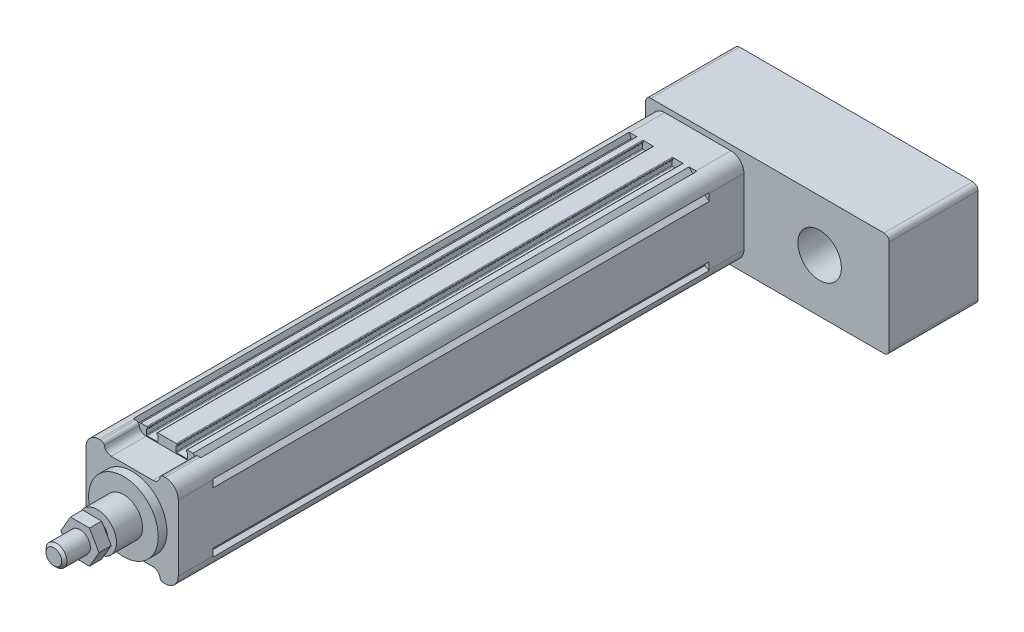
SolidWorks part; units mm, degrees
ref_plane "Front" through (0, 0, 0) normal (0, 0, 1) x (1, 0, 0)
ref_plane "Top" through (0, 0, 0) normal (0, 1, 0) x (1, 0, 0)
ref_plane "Right" through (0, 0, 0) normal (1, 0, 0) x (0, 0, -1)
sketch "草图1" plane through (0, 0, 0) normal (0, 0, 1) x (1, 0, 0)
  line L0 (19.7737, 3) -> (23.3, 3)
  line L1 (23.3, 3) -> (23.3, -3)
  line L2 (23.3, -3) -> (19.7737, -3)
  line L3 (-19.7737, -3) -> (-23.3, -3)
  line L4 (-23.3, -3) -> (-23.3, 3)
  line L5 (-23.3, 3) -> (-19.7737, 3)
  line L6 (-18.2, 24) -> (-19.4434, 26.4869)
  line L7 (-26.4869, 19.4434) -> (-24, 18.2)
  line L8 (-24, 18.2) -> (-24, 17.1)
  line L9 (-24, 17.1) -> (-26.5, 15)
  line L10 (-26.5, 15) -> (-26.5, -15)
  line L11 (-26.5, -15) -> (-24, -17.1)
  line L12 (-24, -17.1) -> (-24, -18.2)
  line L13 (-24, -18.2) -> (-26.4869, -19.4434)
  line L14 (-19.4434, -26.4869) -> (-18.2, -24)
  line L15 (-18.2, -24) -> (-17.1, -24)
  line L16 (-17.1, -24) -> (-15, -26.5)
  line L17 (-15, -26.5) -> (-11.65, -26.5)
  line L18 (-11.25, -26.1) -> (-11.25, -25.6)
  line L19 (-11.65, -25.2) -> (-11.75, -25.2)
  line L20 (-11.75, -25.2) -> (-11.75, -22.4)
  line L21 (-11.35, -22) -> (-5.65, -22)
  line L22 (-5.25, -22.4) -> (-5.25, -25.2)
  line L23 (-5.25, -25.2) -> (-5.35, -25.2)
  line L24 (-5.75, -25.6) -> (-5.75, -26.1)
  line L25 (-5.35, -26.5) -> (5.35, -26.5)
  line L26 (5.75, -26.1) -> (5.75, -25.6)
  line L27 (5.35, -25.2) -> (5.25, -25.2)
  line L28 (5.25, -25.2) -> (5.25, -22.4)
  line L29 (5.65, -22) -> (11.35, -22)
  line L30 (11.75, -22.4) -> (11.75, -25.2)
  line L31 (11.75, -25.2) -> (11.65, -25.2)
  line L32 (11.25, -25.6) -> (11.25, -26.1)
  line L33 (11.65, -26.5) -> (15, -26.5)
  line L34 (15, -26.5) -> (17.1, -24)
  line L35 (17.1, -24) -> (18.2, -24)
  line L36 (18.2, -24) -> (19.4434, -26.4869)
  line L37 (26.4869, -19.4434) -> (24, -18.2)
  line L38 (24, -18.2) -> (24, -17.1)
  line L39 (24, -17.1) -> (26.5, -15)
  line L40 (26.5, -15) -> (26.5, 15)
  line L41 (26.5, 15) -> (24, 17.1)
  line L42 (24, 17.1) -> (24, 18.2)
  line L43 (24, 18.2) -> (26.4869, 19.4434)
  line L44 (19.4434, 26.4869) -> (18.2, 24)
  line L45 (18.2, 24) -> (17.1, 24)
  line L46 (17.1, 24) -> (15, 26.5)
  line L47 (15, 26.5) -> (11.65, 26.5)
  line L48 (11.25, 26.1) -> (11.25, 25.6)
  line L49 (11.65, 25.2) -> (11.75, 25.2)
  line L50 (11.75, 25.2) -> (11.75, 22.4)
  line L51 (11.35, 22) -> (5.65, 22)
  line L52 (5.25, 22.4) -> (5.25, 25.2)
  line L53 (5.25, 25.2) -> (5.35, 25.2)
  line L54 (5.75, 25.6) -> (5.75, 26.1)
  line L55 (5.35, 26.5) -> (-5.35, 26.5)
  line L56 (-5.75, 26.1) -> (-5.75, 25.6)
  line L57 (-5.35, 25.2) -> (-5.25, 25.2)
  line L58 (-5.25, 25.2) -> (-5.25, 22.4)
  line L59 (-5.65, 22) -> (-11.35, 22)
  line L60 (-11.75, 22.4) -> (-11.75, 25.2)
  line L61 (-11.75, 25.2) -> (-11.65, 25.2)
  line L62 (-11.25, 25.6) -> (-11.25, 26.1)
  line L63 (-11.65, 26.5) -> (-15, 26.5)
  line L64 (-15, 26.5) -> (-17.1, 24)
  line L65 (-17.1, 24) -> (-18.2, 24)
  arc A0 (19.7737, 3) -> (-19.7737, 3) centre (0, 0) ccw
  arc A1 (-19.7737, -3) -> (19.7737, -3) centre (0, 0) ccw
  circle A2 centre (19, 19) radius 2.1
  circle A3 centre (19, -19) radius 2.1
  circle A4 centre (-19, -19) radius 2.1
  circle A5 centre (-19, 19) radius 2.1
  arc A6 (-19.4434, 26.4869) -> (-26.4869, 19.4434) centre (-19, 19) ccw
  arc A7 (-26.4869, -19.4434) -> (-19.4434, -26.4869) centre (-19, -19) ccw
  arc A8 (-11.65, -26.5) -> (-11.25, -26.1) centre (-11.65, -26.1) ccw
  arc A9 (-11.25, -25.6) -> (-11.65, -25.2) centre (-11.65, -25.6) ccw
  arc A10 (-11.35, -22) -> (-11.75, -22.4) centre (-11.35, -22.4) ccw
  arc A11 (-5.25, -22.4) -> (-5.65, -22) centre (-5.65, -22.4) ccw
  arc A12 (-5.35, -25.2) -> (-5.75, -25.6) centre (-5.35, -25.6) ccw
  arc A13 (-5.75, -26.1) -> (-5.35, -26.5) centre (-5.35, -26.1) ccw
  arc A14 (5.35, -26.5) -> (5.75, -26.1) centre (5.35, -26.1) ccw
  arc A15 (5.75, -25.6) -> (5.35, -25.2) centre (5.35, -25.6) ccw
  arc A16 (5.65, -22) -> (5.25, -22.4) centre (5.65, -22.4) ccw
  arc A17 (11.75, -22.4) -> (11.35, -22) centre (11.35, -22.4) ccw
  arc A18 (11.65, -25.2) -> (11.25, -25.6) centre (11.65, -25.6) ccw
  arc A19 (11.25, -26.1) -> (11.65, -26.5) centre (11.65, -26.1) ccw
  arc A20 (19.4434, -26.4869) -> (26.4869, -19.4434) centre (19, -19) ccw
  arc A21 (26.4869, 19.4434) -> (19.4434, 26.4869) centre (19, 19) ccw
  arc A22 (11.65, 26.5) -> (11.25, 26.1) centre (11.65, 26.1) ccw
  arc A23 (11.25, 25.6) -> (11.65, 25.2) centre (11.65, 25.6) ccw
  arc A24 (11.35, 22) -> (11.75, 22.4) centre (11.35, 22.4) ccw
  arc A25 (5.25, 22.4) -> (5.65, 22) centre (5.65, 22.4) ccw
  arc A26 (5.35, 25.2) -> (5.75, 25.6) centre (5.35, 25.6) ccw
  arc A27 (5.75, 26.1) -> (5.35, 26.5) centre (5.35, 26.1) ccw
  arc A28 (-5.35, 26.5) -> (-5.75, 26.1) centre (-5.35, 26.1) ccw
  arc A29 (-5.75, 25.6) -> (-5.35, 25.2) centre (-5.35, 25.6) ccw
  arc A30 (-5.65, 22) -> (-5.25, 22.4) centre (-5.65, 22.4) ccw
  arc A31 (-11.75, 22.4) -> (-11.35, 22) centre (-11.35, 22.4) ccw
  arc A32 (-11.65, 25.2) -> (-11.25, 25.6) centre (-11.65, 25.6) ccw
  arc A33 (-11.25, 26.1) -> (-11.65, 26.5) centre (-11.65, 26.1) ccw
extrude "凸台-拉伸1" add sketch "草图1" along normal blind 285
sketch "草图6" plane through (0, 0, 285) normal (0, 0, 1) x (1, 0, 0)
  line L0 (0, 0) -> (19, 0) construction
  line L2 (-26.5, -19) -> (-26.5, 19)
  line L3 (-19, 26.5) -> (-17.9161, 26.5)
  line L4 (26.5, -19) -> (26.5, 19)
  line L5 (-26.5, -26.5) -> (26.5, 26.5) construction
  line L6 (-26.5, 26.5) -> (26.5, -26.5) construction
  line L7 (-12, 21.5) -> (12, 21.5)
  line L9 (19, 26.5) -> (17.9161, 26.5)
  line L10 (19, -26.5) -> (17.9161, -26.5)
  line L11 (-12, -21.5) -> (12, -21.5)
  line L12 (-19, -26.5) -> (-17.9161, -26.5)
  arc A0 (12, 21.5) -> (15.9441, 24.8333) centre (12, 25.5) ccw
  arc A1 (-15.9441, 24.8333) -> (-12, 21.5) centre (-12, 25.5) ccw
  arc A2 (-15.9441, 24.8333) -> (-17.9161, 26.5) centre (-17.9161, 24.5) ccw
  arc A3 (15.9441, 24.8333) -> (17.9161, 26.5) centre (17.9161, 24.5) cw
  arc A4 (-26.5, -19) -> (-19, -26.5) centre (-19, -19) ccw
  arc A5 (19, -26.5) -> (26.5, -19) centre (19, -19) ccw
  arc A6 (26.5, 19) -> (19, 26.5) centre (19, 19) ccw
  arc A7 (-26.5, 19) -> (-19, 26.5) centre (-19, 19) cw
  arc A8 (15.9441, -24.8333) -> (17.9161, -26.5) centre (17.9161, -24.5) ccw
  arc A9 (12, -21.5) -> (15.9441, -24.8333) centre (12, -25.5) cw
  arc A10 (-15.9441, -24.8333) -> (-12, -21.5) centre (-12, -25.5) cw
  arc A11 (-15.9441, -24.8333) -> (-17.9161, -26.5) centre (-17.9161, -24.5) cw
  point P0 (0, 0)
  point P9 (0, 21.5)
  point P13 (20, 20.8461)
  point P16 (-12, 20.8461)
  dimension "D5" = 4
  dimension "D6" = 2
  dimension "D7" = 2
  dimension "D9" = 7.5
  dimension "D1" = 53
  dimension "D2" = 53
  dimension "D3" = 26.5
  dimension "D4" = 24
  dimension "D8" = 5
extrude "凸台-拉伸2" add sketch "草图6" along normal blind 20
sketch "草图7" plane through (0, 0, 305) normal (0, 0, 1) x (1, 0, 0)
  circle A0 centre (0, 0) radius 20
  dimension "D1" = 40
extrude "凸台-拉伸3" add sketch "草图7" along normal blind 5
sketch "草图9" plane through (0, 0, 310) normal (0, 0, 1) x (1, 0, 0)
  circle A0 centre (0, 0) radius 11
  dimension "D1" = 22
extrude "凸台-拉伸4" add sketch "草图9" along normal blind 15
sketch "草图10" plane through (0, 0, 325) normal (0, 0, 1) x (1, 0, 0)
  circle A0 centre (0, 0) radius 6
  dimension "D1" = 12
extrude "凸台-拉伸5" add sketch "草图10" along normal blind 25
sketch "草图11" plane through (0, 0, 0) normal (0, 0, -1) x (-1, 0, 0)
  line L1 (-19, -26.5) -> (19, -26.5)
  line L2 (-26.5, -19) -> (-26.5, 19)
  line L3 (-19, 26.5) -> (19, 26.5)
  line L4 (26.5, -19) -> (26.5, 19)
  line L5 (-26.5, -26.5) -> (26.5, 26.5) construction
  line L6 (-26.5, 26.5) -> (26.5, -26.5) construction
  arc A0 (-26.5, -19) -> (-19, -26.5) centre (-19, -19) ccw
  arc A1 (19, -26.5) -> (26.5, -19) centre (19, -19) ccw
  arc A2 (26.5, 19) -> (19, 26.5) centre (19, 19) ccw
  arc A3 (-26.5, 19) -> (-19, 26.5) centre (-19, 19) cw
  point P0 (0, 0)
  dimension "D3" = 7.5
  dimension "D1" = 53
  dimension "D2" = 53
extrude "凸台-拉伸6" add sketch "草图11" along normal blind 20
sketch "草图12" plane through (0, 0, -20) normal (0, 0, -1) x (-1, 0, 0)
  line L1 (-107, -30.4042) -> (27, -30.4042)
  line L2 (-110, -27.4042) -> (-110, 26.5958)
  line L3 (-107, 29.5958) -> (27, 29.5958)
  line L4 (30, -27.4042) -> (30, 26.5958)
  line L5 (-110, -30.4042) -> (30, 29.5958) construction
  line L6 (-110, 29.5958) -> (30, -30.4042) construction
  arc A0 (27, 29.5958) -> (30, 26.5958) centre (27, 26.5958) cw
  arc A1 (30, -27.4042) -> (27, -30.4042) centre (27, -27.4042) cw
  arc A2 (-110, -27.4042) -> (-107, -30.4042) centre (-107, -27.4042) ccw
  arc A3 (-110, 26.5958) -> (-107, 29.5958) centre (-107, 26.5958) cw
  point P0 (-40, -0.4042)
  dimension "D4" = 3
  dimension "D1" = 60
  dimension "D2" = 140
  dimension "D3" = 30
extrude "凸台-拉伸7" add sketch "草图12" along normal blind 51
sketch "草图13" plane through (0, 0, -20) normal (0, 0, 1) x (1, 0, 0)
  circle A0 centre (70, 0) radius 12.5
  dimension "D2" = 25
  dimension "D1" = 70
extrude "切除-拉伸2" cut sketch "草图13" against normal blind 30
hole_wizard "M6 螺纹孔1" positions "草图14" profile "草图15" tap size "M6" standard "GB"
sketch "草图14" plane through (0, 0, -71) normal (0, 0, -1) x (-1, 0, 0)
  line L0 (30, -27.4042) -> (30, 26.5958) construction
  point P0 (19, -19)
  dimension "D1" = 11
  dimension "D2" = 19
sketch "草图15" plane through (-19, -19, -71) normal (1, 0, 0) x (0, 1, 0)
  line L0 (0, 0) -> (0, 16.5022)
  line L1 (0, 16.5022) -> (2.5, 15)
  line L2 (2.5, 15) -> (2.5, 0)
  line L5 (2.5, 0) -> (0, 0)
  line L10 (0, 16.5022) -> (-2.5, 15) construction
  line L11 (0, -6.35) -> (0, 107.95) construction
  dimension "螺纹孔钻头直径" = 5
  dimension "螺纹孔钻头深度" = 15
  dimension "导头角度" = 118
cosmetic thread "孔螺蚊线4" parameters "D1"=12, "D2"=6
pattern_linear "阵列(线性)1" count 2 spacing 38 along (0, 1, 0) count 2 spacing 38 along (1, 0, 0) of "M6 螺纹孔1"
hole_wizard "M6 螺纹孔2" positions "草图16" profile "草图17" tap size "M6" standard "GB"
sketch "草图16" plane through (0, 0, -71) normal (0, 0, -1) x (-1, 0, 0)
  circle A1 centre (-19, 19) radius 2.5 construction
  circle A2 centre (-19, -19) radius 2.5 construction
  point P0 (-84, -19)
  point P2 (-84, 19)
  dimension "D3" = 65
  dimension "D1" = 19
  dimension "D2" = 19
  dimension "D4" = 65
sketch "草图17" plane through (84, -19, -71) normal (1, 0, 0) x (0, 1, 0)
  line L0 (0, 0) -> (0, 16.5022)
  line L1 (0, 16.5022) -> (2.5, 15)
  line L2 (2.5, 15) -> (2.5, 0)
  line L5 (2.5, 0) -> (0, 0)
  line L10 (0, 16.5022) -> (-2.5, 15) construction
  line L11 (0, -6.35) -> (0, 107.95) construction
  dimension "螺纹孔钻头直径" = 5
  dimension "螺纹孔钻头深度" = 15
  dimension "导头角度" = 118
cosmetic thread "孔螺蚊线5" parameters "D1"=12, "D2"=6
cosmetic thread "孔螺蚊线6" parameters "D1"=12, "D2"=6
hole_wizard "M6 螺纹孔3" positions "草图19" profile "草图20" tap size "M6" standard "GB"
sketch "草图19" plane through (-26.5, 0, 0) normal (-1, 0, 0) x (0, 0, 1)
  line L0 (305, 19) -> (305, -19) construction
  point P0 (295, 11)
  point P2 (295, -11)
  dimension "D1" = 10
  dimension "D2" = 10
  dimension "D3" = 22
  dimension "D4" = 11
sketch "草图20" plane through (-26.5, 11, 295) normal (0, 1, 0) x (0, 0, 1)
  line L0 (0, 0) -> (0, 16.5022)
  line L1 (0, 16.5022) -> (2.5, 15)
  line L2 (2.5, 15) -> (2.5, 0)
  line L5 (2.5, 0) -> (0, 0)
  line L10 (0, 16.5022) -> (-2.5, 15) construction
  line L11 (0, -6.35) -> (0, 107.95) construction
  dimension "螺纹孔钻头直径" = 5
  dimension "螺纹孔钻头深度" = 15
  dimension "导头角度" = 118
cosmetic thread "孔螺蚊线7" parameters "D1"=12, "D2"=6
cosmetic thread "孔螺蚊线8" parameters "D1"=12, "D2"=6
hole_wizard "M6 螺纹孔4" positions "草图21" profile "草图22" tap size "M6" standard "GB"
sketch "草图21" plane through (-26.5, 0, 0) normal (-1, 0, 0) x (0, 0, 1)
  line L0 (-20, -27.4042) -> (-20, 26.5958) construction
  line L1 (-20, -19) -> (-20, 19) construction
  point P0 (-10, 11)
  point P2 (-10, -11)
  dimension "D1" = 10
  dimension "D2" = 10
  dimension "D3" = 11
  dimension "D4" = 11
sketch "草图22" plane through (-26.5, 11, -10) normal (0, 1, 0) x (0, 0, 1)
  line L0 (0, 0) -> (0, 16.5022)
  line L1 (0, 16.5022) -> (2.5, 15)
  line L2 (2.5, 15) -> (2.5, 0)
  line L5 (2.5, 0) -> (0, 0)
  line L10 (0, 16.5022) -> (-2.5, 15) construction
  line L11 (0, -6.35) -> (0, 107.95) construction
  dimension "螺纹孔钻头直径" = 5
  dimension "螺纹孔钻头深度" = 15
  dimension "导头角度" = 118
cosmetic thread "孔螺蚊线9" parameters "D1"=12, "D2"=6
cosmetic thread "孔螺蚊线10" parameters "D1"=12, "D2"=6
chamfer "倒角1" distance 1.5 angle 45 1 edges at (6, 0, 350)
sketch "草图23" plane through (0, 0, 325) normal (0, 0, 1) x (1, 0, 0)
  line L1 (10.9697, 0) -> (5.4848, 9.5)
  line L2 (5.4848, 9.5) -> (-5.4848, 9.5)
  line L3 (-5.4848, 9.5) -> (-10.9697, 0)
  line L4 (-10.9697, 0) -> (-5.4848, -9.5)
  line L5 (-5.4848, -9.5) -> (5.4848, -9.5)
  line L6 (5.4848, -9.5) -> (10.9697, 0)
  circle A0 centre (0, 0) radius 9.5 construction
  dimension "D1" = 19
extrude "凸台-拉伸8" add sketch "草图23" along normal blind 7 from offset 3
